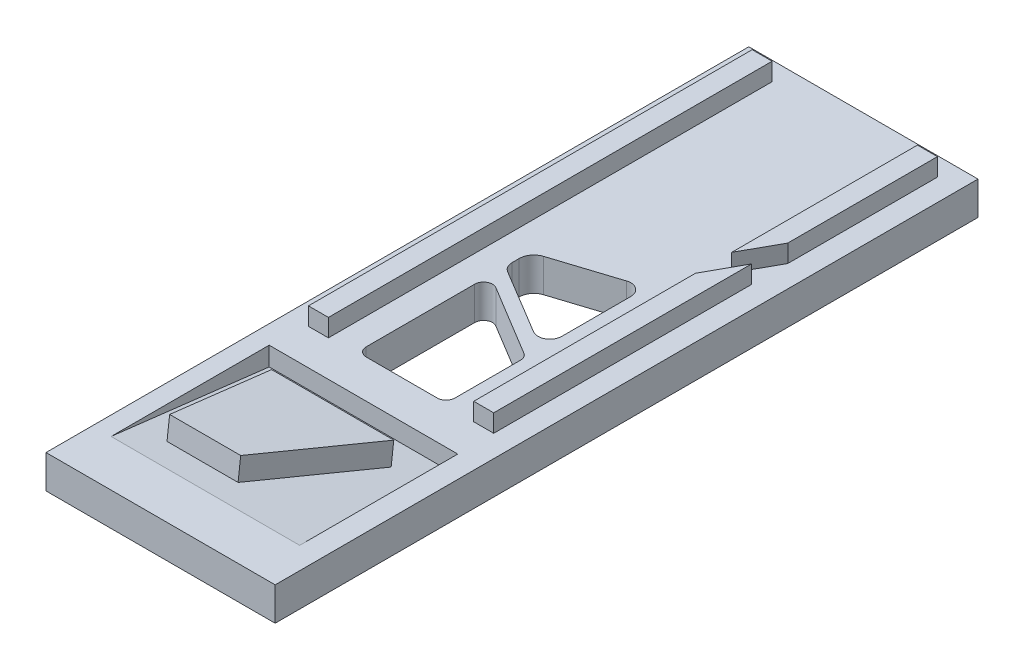
SolidWorks part; units mm, degrees
ref_plane "前视基准面" through (0, 0, 0) normal (0, 0, 1) x (1, 0, 0)
ref_plane "上视基准面" through (0, 0, 0) normal (0, 1, 0) x (1, 0, 0)
ref_plane "右视基准面" through (0, 0, 0) normal (1, 0, 0) x (0, 0, -1)
sketch "草图1" plane through (0, 0, 0) normal (0, 1, 0) x (1, 0, 0)
  line L1 (0, 0) -> (10.65, 0)
  line L2 (0, 0) -> (0, -32)
  line L3 (0, -32) -> (10.65, -32)
  line L4 (10.65, 0) -> (10.65, -32)
  dimension "D1" = 32
  dimension "D2" = 10.65
extrude "凸台-拉伸1" add sketch "草图1" along normal blind 1.5
sketch "草图3" plane through (0, 0, 0) normal (-1, 0, 0) x (0, 0, 1)
  line L0 (22.6197, 1.5) -> (29.7459, 1.5)
  line L1 (0, 1.5) -> (32, 1.5) construction
  line L2 (29.7459, 1.5) -> (22.6197, 0.65)
  line L3 (22.6197, 0.65) -> (22.6197, 1.5)
  dimension "D1" = 0.85
extrude "切除-拉伸1" cut sketch "草图3" against normal blind 8.5 from offset 1 offset against normal yes
sketch "草图4" plane through (0, 1.5, 0) normal (0, 1, 0) x (1, 0, 0)
  line L0 (5.325, 0) -> (5.325, -18.3684) construction
  line L1 (2.05, -1) -> (1.15, -1)
  line L2 (2.05, -1) -> (2.05, -21)
  line L3 (2.05, -21) -> (1.15, -21)
  line L4 (1.15, -1) -> (1.15, -21)
  line L5 (8.6, -1) -> (9.5, -1)
  line L6 (8.6, -1) -> (8.6, -21)
  line L7 (8.6, -21) -> (9.5, -21)
  line L8 (9.5, -1) -> (9.5, -21)
  line L9 (10.65, 0) -> (0, 0) construction
  line L10 (9.5, -29.7459) -> (9.5, -22.6197) construction
  dimension "D1" = 0.9
  dimension "D2" = 0.9
  dimension "D3" = 1
  dimension "D4" = 1
  dimension "D5" = 20
  dimension "D6" = 20
extrude "凸台-拉伸2" add sketch "草图4" along normal blind 0.8
sketch "草图5" plane through (0, 1.5, 0) normal (0, 1, 0) x (1, 0, 0)
  line L0 (3.25, -15.6041) -> (3.25, -20.4952)
  line L1 (3.65, -20.8952) -> (6.85, -20.8952)
  line L2 (7.25, -20.4952) -> (7.25, -17.5369)
  line L3 (7.0568, -17.1945) -> (3.8568, -15.2617)
  line L4 (5.25, -22.6197) -> (5.25, -18.0531) construction
  line L5 (9.5, -22.6197) -> (1, -22.6197) construction
  line L6 (3.5103, -14.3805) -> (6.4363, -16.1394)
  line L7 (7.25, -15.6792) -> (7.25, -12.5694)
  line L8 (6.5488, -12.0581) -> (3.7131, -12.9686)
  line L9 (3.25, -13.6037) -> (3.25, -13.9202)
  arc A0 (3.25, -15.6041) -> (3.8568, -15.2617) centre (3.65, -15.6041) cw
  arc A1 (7.25, -17.5369) -> (7.0568, -17.1945) centre (6.85, -17.5369) ccw
  arc A2 (3.65, -20.8952) -> (3.25, -20.4952) centre (3.65, -20.4952) cw
  arc A3 (6.85, -20.8952) -> (7.25, -20.4952) centre (6.85, -20.4952) ccw
  arc A4 (3.25, -13.6037) -> (3.7131, -12.9686) centre (3.917, -13.6037) cw
  arc A5 (3.25, -13.9202) -> (3.5103, -14.3805) centre (3.787, -13.9202) ccw
  arc A6 (7.25, -12.5694) -> (6.5488, -12.0581) centre (6.713, -12.5694) ccw
  arc A7 (6.4363, -16.1394) -> (7.25, -15.6792) centre (6.713, -15.6792) ccw
  point P10 (3.25, -14.8952)
  point P15 (3.25, -20.8952)
  point P18 (7.25, -20.8952)
  dimension "D3" = 0.4
  dimension "D4" = 0.4
  dimension "D5" = 0.4
  dimension "D6" = 0.4
  dimension "D7" = 0.667
  dimension "D8" = 0.537
  dimension "D9" = 0.537
  dimension "D10" = 0.537
  dimension "D1" = 4
  dimension "D2" = 6
extrude "切除-拉伸2" cut sketch "草图5" against normal blind 5.8
sketch "草图6" plane through (0, 2.3, 0) normal (0, 1, 0) x (1, 0, 0)
  line L0 (9.5, -7.7442) -> (8.6, -9.3701)
  line L1 (9.5, -21) -> (9.5, -1) construction
  line L2 (8.6, -1) -> (8.6, -21) construction
  line L3 (8.6, -9.3701) -> (8.6, -11)
  line L4 (8.6, -11) -> (9.5, -9.3741)
  line L5 (9.5, -9.3741) -> (9.5, -7.7442)
extrude "切除-拉伸3" cut sketch "草图6" against normal up to vertex (0.8 mm away)
sketch "草图7" plane through (0, -2.0193, 0.2409) normal (0, 0.993, -0.1184) x (1, 0, 0)
  line L0 (2.3084, -23.8639) -> (7.8146, -23.8639)
  line L1 (7.8146, -23.8639) -> (5.512, -28.4941)
  line L2 (5.512, -28.4941) -> (2.3084, -28.4941)
  line L3 (2.3084, -28.4941) -> (2.3084, -23.8639)
extrude "凸台-拉伸3" add sketch "草图7" along normal blind 1
sketch "草图8" plane through (0, 1.5, 0) normal (0, 1, 0) x (1, 0, 0)
  line L0 (0.16, -0.16) -> (0.16, -31.84)
  line L1 (0, 0) -> (10.65, 0)
  line L2 (0, 0) -> (0, -32)
  line L3 (0, -32) -> (10.65, -32)
  line L4 (10.65, 0) -> (10.65, -32)
  line L5 (0.16, -31.84) -> (10.49, -31.84)
  line L6 (10.49, -0.16) -> (10.49, -31.84)
  line L7 (0.16, -0.16) -> (10.49, -0.16)
  dimension "D1" = 0.16
extrude "切除-拉伸4" cut sketch "草图8" against normal blind 10
